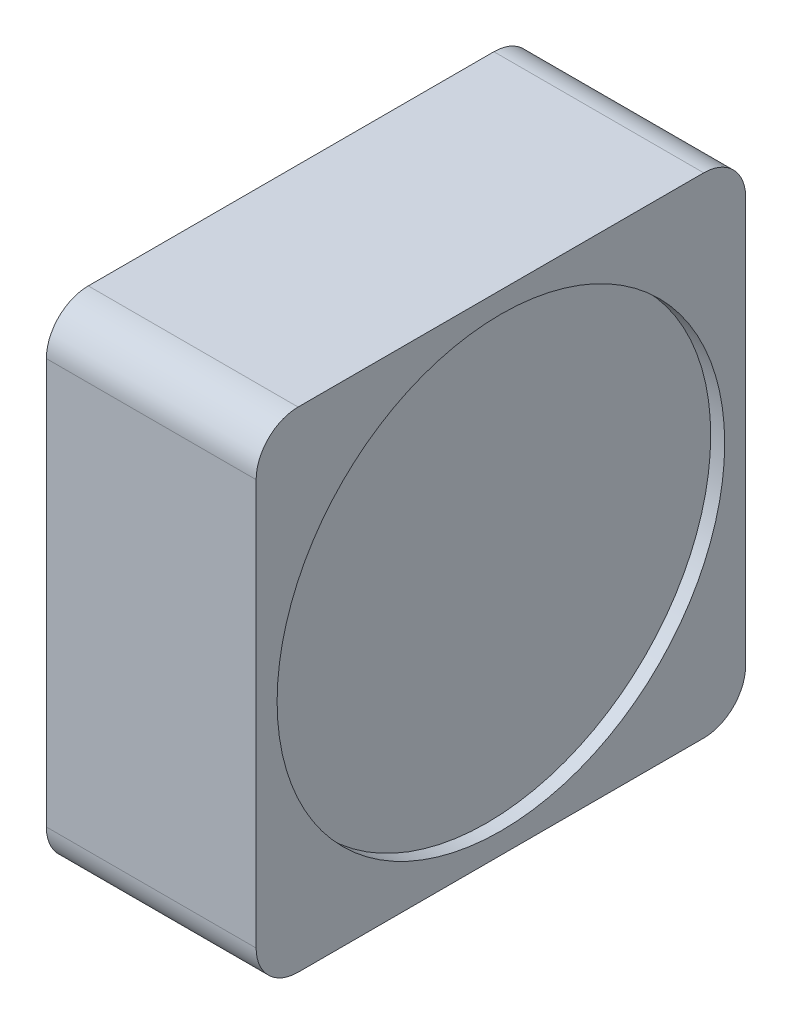
SolidWorks part; units mm, degrees
ref_plane "Front Plane" through (0, 0, 0) normal (0, 0, 1) x (1, 0, 0)
ref_plane "Top Plane" through (0, 0, 0) normal (0, 1, 0) x (1, 0, 0)
ref_plane "Right Plane" through (0, 0, 0) normal (1, 0, 0) x (0, 0, -1)
sketch "Çizim1" plane through (0, 0, 0) normal (1, 0, 0) x (0, 0, -1)
  line L1 (-175, -175) -> (175, -175)
  line L2 (-175, -175) -> (-175, 175)
  line L3 (-175, 175) -> (175, 175)
  line L4 (175, -175) -> (175, 175)
  line L5 (-175, -175) -> (175, 175) construction
  line L6 (-175, 175) -> (175, -175) construction
  point P0 (0, 0)
  dimension "D1" = 350
  dimension "D2" = 350
extrude "Yükseklik-Ekstrüzyon1" add sketch "Çizim1" along normal blind 150
sketch "Çizim2" plane through (150, 0, 0) normal (1, 0, 0) x (0, 0, -1)
  circle A0 centre (0, 0) radius 160
  dimension "D1" = 320
extrude "Kes-Ekstrüzyon1" cut sketch "Çizim2" against normal blind 10
fillet "Radyus1" radius 30 4 edges at (75, -175, -175) (75, -175, 175) (75, 175, 175) (75, 175, -175)
scale "Ölçek2" scale about centroid uniform scaling yes scale factor 1
